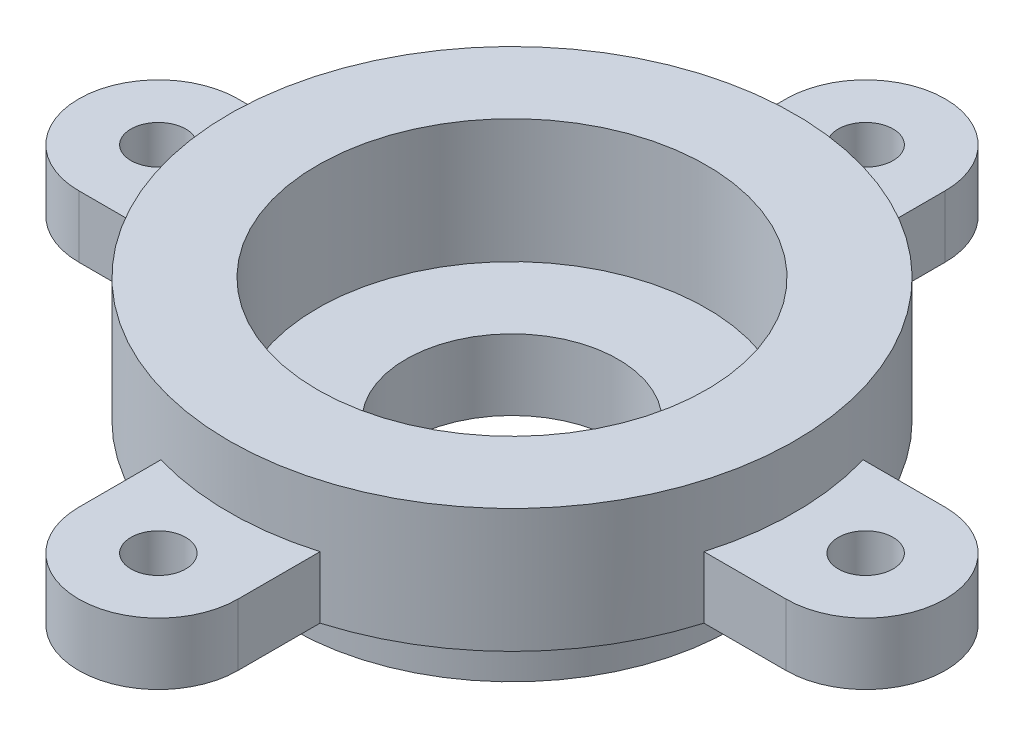
SolidWorks part; units mm, degrees
ref_plane "Front Plane" through (0, 0, 0) normal (0, 0, 1) x (1, 0, 0)
ref_plane "Top Plane" through (0, 0, 0) normal (0, 1, 0) x (1, 0, 0)
ref_plane "Right Plane" through (0, 0, 0) normal (1, 0, 0) x (0, 0, -1)
sketch "Sketch1" plane through (0, 0, 0) normal (0, 1, 0) x (1, 0, 0)
  circle A0 centre (0, 0) radius 12.45
  circle A1 centre (0, 0) radius 6
  dimension "D1" = 24.9
  dimension "D2" = 12
extrude "Boss-Extrude1" add sketch "Sketch1" along normal blind 4
sketch "Sketch2" plane through (0, 4, 0) normal (0, 1, 0) x (1, 0, 0)
  circle A0 centre (0, 0) radius 16
  circle A1 centre (0, 0) radius 11
  dimension "D1" = 32
  dimension "D2" = 22
extrude "Boss-Extrude2" add sketch "Sketch2" along normal blind 7
sketch "Sketch3" plane through (0, 11, 0) normal (0, 1, 0) x (1, 0, 0)
  line L0 (-4.5, 20) -> (-4.5, 15.3542)
  line L1 (4.5, 20) -> (4.5, 15.3542)
  arc A0 (4.5, 20) -> (-4.5, 20) centre (0, 20) ccw
  circle A1 centre (0, 0) radius 16 construction
  arc A2 (4.5, 15.3542) -> (-4.5, 15.3542) centre (0, 0) ccw
  circle A3 centre (0, 20) radius 1.55
  dimension "D1" = 9
  dimension "D3" = 3.1
  dimension "D2" = 20
extrude "Boss-Extrude3" add sketch "Sketch3" along normal blind 3.5 from surface at -7 starting at face at (0, 4, 12.45)
pattern_circular "CirPattern1" count 4 over 360 about axis through (0, 0, 0) along (0, 1, 0) of "Boss-Extrude3"
